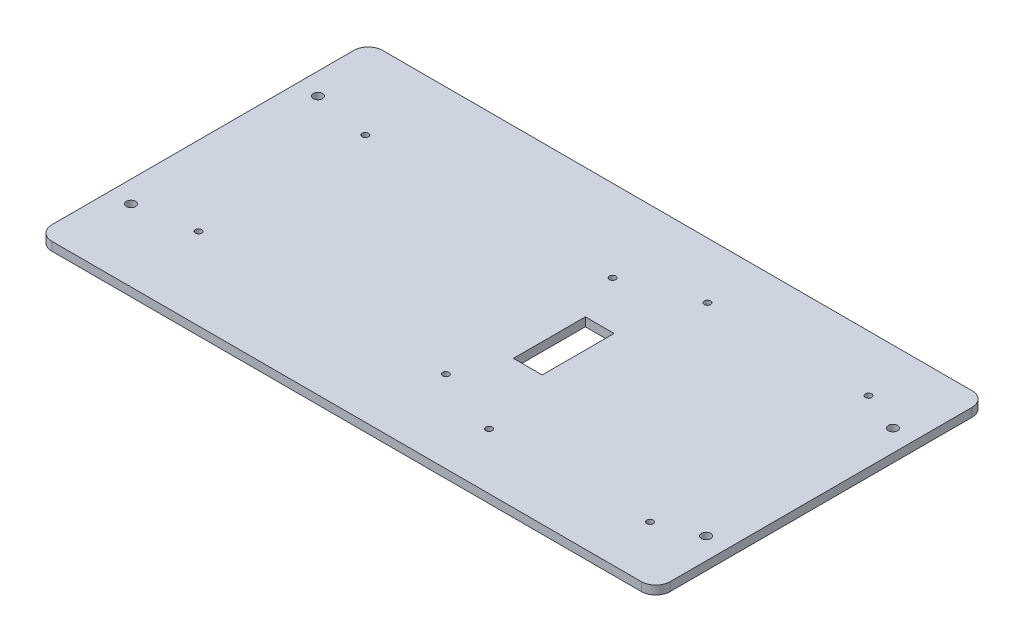
SolidWorks part; units mm, degrees
ref_plane "Front Plane" through (0, 0, 0) normal (0, 0, 1) x (1, 0, 0)
ref_plane "Top Plane" through (0, 0, 0) normal (0, 1, 0) x (1, 0, 0)
ref_plane "Right Plane" through (0, 0, 0) normal (1, 0, 0) x (0, 0, -1)
sketch "Sketch1" plane through (0, 0, 0) normal (0, 1, 0) x (1, 0, 0)
  line L0 (107.5, 0) -> (-107.5, 0) construction
  line L1 (-107.5, -57.5) -> (107.5, -57.5)
  line L2 (-107.5, -57.5) -> (-107.5, 57.5)
  line L3 (-107.5, 57.5) -> (107.5, 57.5)
  line L4 (107.5, -57.5) -> (107.5, 57.5)
  line L5 (-107.5, -57.5) -> (107.5, 57.5) construction
  line L6 (-107.5, 57.5) -> (107.5, -57.5) construction
  line L7 (0, -57.5) -> (0, 57.5) construction
  line L9 (13, -12.5) -> (23, -12.5)
  line L10 (13, -12.5) -> (13, 12.5)
  line L11 (13, 12.5) -> (23, 12.5)
  line L12 (23, -12.5) -> (23, 12.5)
  line L13 (13, -12.5) -> (23, 12.5) construction
  line L14 (13, 12.5) -> (23, -12.5) construction
  circle A0 centre (100, -32.5) radius 1.6
  circle A1 centre (-100, -32.5) radius 1.6
  circle A2 centre (100, 32.5) radius 1.6
  circle A3 centre (-100, 32.5) radius 1.6
  circle A4 centre (-80, 29) radius 1.1
  circle A7 centre (-80, -29) radius 1.1
  circle A9 centre (30, 38) radius 1.1
  circle A10 centre (86, 38) radius 1.1
  circle A11 centre (86, -38) radius 1.1
  circle A12 centre (30, -38) radius 1.1
  circle A13 centre (6, 29) radius 1.1
  circle A14 centre (6, -29) radius 1.1
  point P0 (0, 0)
  point P30 (18, 0)
  dimension "D3" = 3.2
  dimension "D6" = 2.2
  dimension "D9" = 2.2
  dimension "D11" = 2.2
  dimension "D12" = 2.2
  dimension "D8" = 18
  dimension "D1" = 115
  dimension "D2" = 215
  dimension "D4" = 7.5
  dimension "D5" = 25
  dimension "D7" = 29
  dimension "D10" = 6
  dimension "D13" = 56
  dimension "D14" = 30
  dimension "D15" = 38
  dimension "D16" = 10
  dimension "D17" = 25
  dimension "D18" = 80
  dimension "D19" = 29
extrude "Boss-Extrude1" add sketch "Sketch1" along normal blind 3
fillet "Fillet1" radius 5 4 edges at (-107.5, 1.5, -57.5) (107.5, 1.5, -57.5) (107.5, 1.5, 57.5) (-107.5, 1.5, 57.5)
